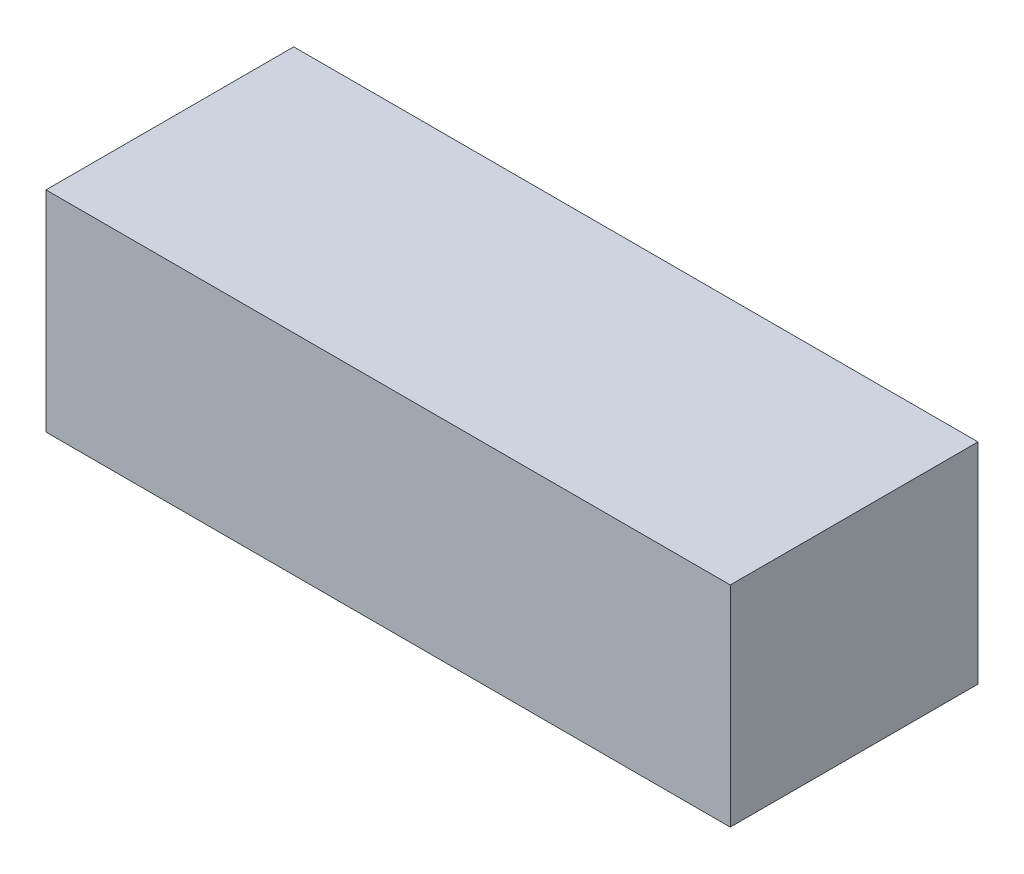
SolidWorks part; units mm, degrees
ref_plane "前视基准面" through (0, 0, 0) normal (0, 0, 1) x (1, 0, 0)
ref_plane "上视基准面" through (0, 0, 0) normal (0, 1, 0) x (1, 0, 0)
ref_plane "右视基准面" through (0, 0, 0) normal (1, 0, 0) x (0, 0, -1)
sketch "Sketch1" plane through (0, 0, 0) normal (0, 0, 1) x (1, 0, 0)
  line L1 (-44.6045, 8.3463) -> (92.3955, 8.3463)
  line L2 (-44.6045, 8.3463) -> (-44.6045, -33.6537)
  line L3 (-44.6045, -33.6537) -> (92.3955, -33.6537)
  line L4 (92.3955, 8.3463) -> (92.3955, -33.6537)
extrude "Boss-Extrude1" add sketch "Sketch1" along normal blind 49.6
